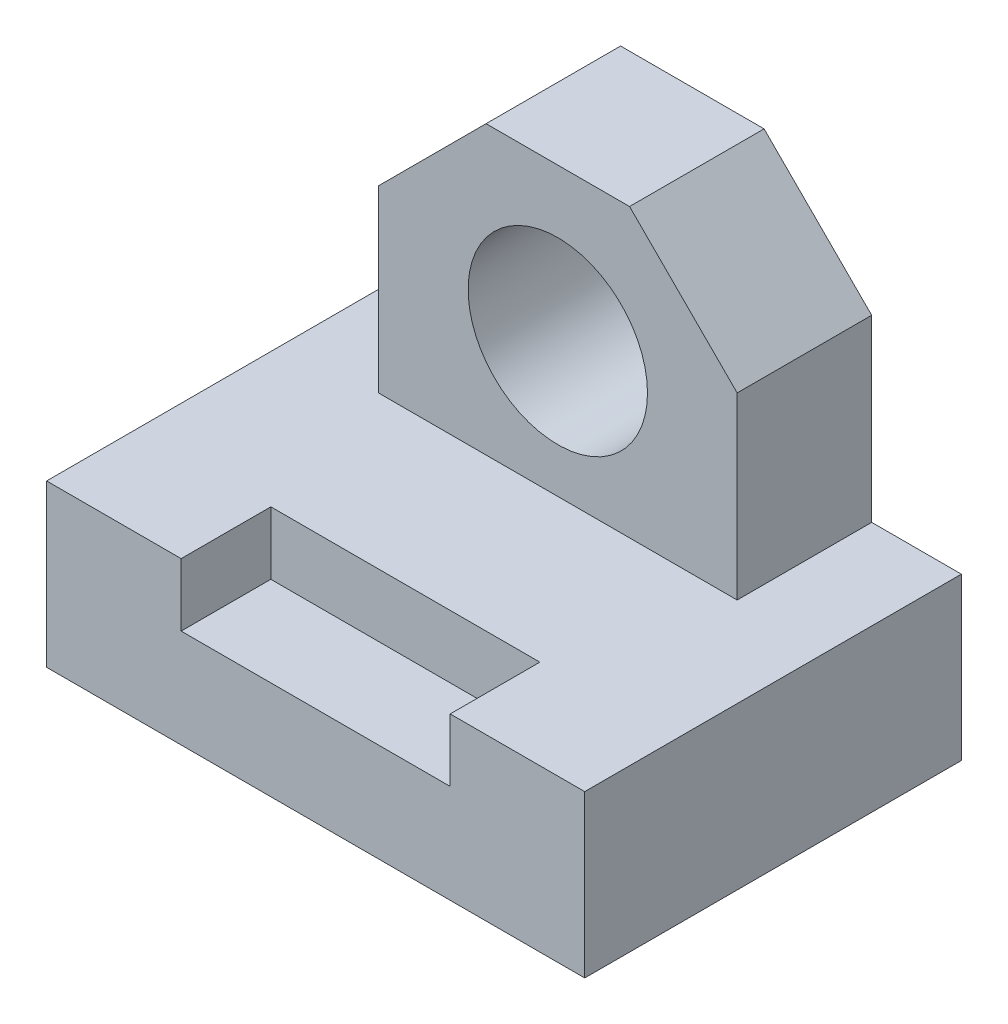
SolidWorks part; units mm, degrees
material "Plain Carbon Steel"
ref_plane "Front Plane" through (0, 0, 0) normal (0, 0, 1) x (1, 0, 0)
ref_plane "Top Plane" through (0, 0, 0) normal (0, 1, 0) x (1, 0, 0)
ref_plane "Right Plane" through (0, 0, 0) normal (1, 0, 0) x (0, 0, -1)
sketch "Sketch1" plane through (0, 0, 0) normal (0, 0, 1) x (1, 0, 0)
  line L0 (-30, 0) -> (30, 0)
  line L1 (30, 0) -> (30, 18)
  line L2 (30, 18) -> (-30, 18)
  line L3 (-30, 18) -> (-30, 0)
  point P5 (0, 0)
  dimension "D1" = 60
  dimension "D2" = 18
extrude "Boss-Extrude1" add sketch "Sketch1" along normal blind 42
sketch "Sketch2" plane through (0, 18, 0) normal (0, 1, 0) x (1, 0, 0)
  line L0 (0, 0) -> (0, -42) construction
  line L1 (30, -42) -> (-30, -42) construction
  line L3 (-15, -32) -> (15, -32)
  line L4 (15, -32) -> (15, -42)
  line L5 (15, -42) -> (-15, -42)
  line L6 (-15, -42) -> (-15, -32)
  dimension "D1" = 30
  dimension "D2" = 10
extrude "Cut-Extrude1" cut sketch "Sketch2" against normal blind 7
sketch "Sketch3" plane through (0, 0, 0) normal (0, 0, -1) x (-1, 0, 0)
  line L0 (0, 0) -> (0, 50) construction
  line L2 (20, 18) -> (20, 38)
  line L3 (-30, 18) -> (30, 18) construction
  line L4 (20, 38) -> (8, 50)
  line L5 (8, 50) -> (-8, 50)
  line L6 (-8, 50) -> (-20, 38)
  line L7 (-20, 38) -> (-20, 18)
  line L8 (-20, 18) -> (20, 18)
  line L9 (30, 0) -> (-30, 0) construction
  dimension "D1" = 40
  dimension "D2" = 16
  dimension "D3" = 50
  dimension "D4" = 12
extrude "Boss-Extrude2" add sketch "Sketch3" against normal blind 15
sketch "Sketch4" plane through (0, 0, 15) normal (0, 0, 1) x (1, 0, 0)
  line L0 (0, 18) -> (0, 50) construction
  line L1 (20, 18) -> (-20, 18) construction
  line L2 (-8, 50) -> (8, 50) construction
  circle A0 centre (0, 33) radius 10
  dimension "D1" = 20
  dimension "D2" = 15
extrude "Cut-Extrude2" cut sketch "Sketch4" against normal through all
